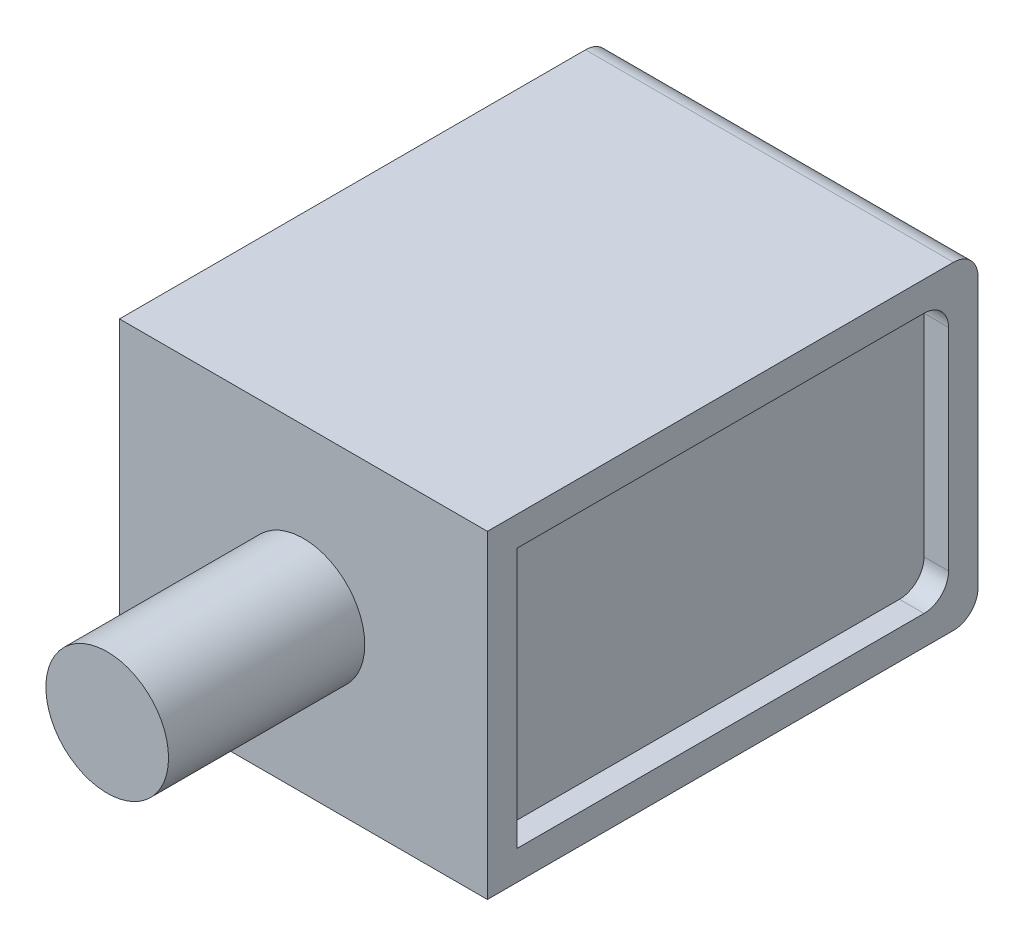
SolidWorks part; units mm, degrees
ref_plane "Plan de face" through (0, 0, 0) normal (0, 0, 1) x (1, 0, 0)
ref_plane "Plan de dessus" through (0, 0, 0) normal (0, 1, 0) x (1, 0, 0)
ref_plane "Plan de droite" through (0, 0, 0) normal (1, 0, 0) x (0, 0, -1)
sketch "Esquisse1" plane through (0, 0, 0) normal (0, 0, 1) x (1, 0, 0)
  line L1 (7.5, -6.5) -> (-7.5, -6.5)
  line L2 (7.5, -6.5) -> (7.5, 6.5)
  line L3 (7.5, 6.5) -> (-7.5, 6.5)
  line L4 (-7.5, -6.5) -> (-7.5, 6.5)
  line L5 (7.5, -6.5) -> (-7.5, 6.5) construction
  line L6 (7.5, 6.5) -> (-7.5, -6.5) construction
  point P0 (0, 0)
  dimension "D1" = 13
  dimension "D2" = 15
extrude "Boss.-Extru.1" add sketch "Esquisse1" along normal mid plane 20
fillet "Congé1" radius 1 2 edges at (0, -6.5, -10) (0, 6.5, -10)
sketch "Esquisse2" plane through (7.5, 0, 0) normal (1, 0, 0) x (0, 0, -1)
  line L8 (-8.8, -5.3) -> (8.8, -5.3)
  line L9 (8.8, -5.3) -> (8.8, 5.3)
  line L10 (8.8, 5.3) -> (-8.8, 5.3)
  line L11 (-8.8, 5.3) -> (-8.8, -5.3)
  line L12 (-8.8, -5.3) -> (8.8, -5.3)
  line L13 (8.8, -5.3) -> (8.8, 5.3)
  line L14 (8.8, 5.3) -> (-8.8, 5.3)
  line L15 (-8.8, 5.3) -> (-8.8, -5.3)
  dimension "D1" = 1.2
extrude "Enlèv. mat.-Extru.1" cut sketch "Esquisse2" against normal blind 1
fillet "Congé2" radius 1 2 edges at (7, -5.3, -8.8) (7, 5.3, -8.8)
mirror "Symétrie1" about plane through (0, 0, 0) normal (1, 0, 0) of "Congé2", "Enlèv. mat.-Extru.1"
sketch "Esquisse3" plane through (0, 0, 10) normal (0, 0, 1) x (1, 0, 0)
  circle A0 centre (0, 0) radius 2.5
  dimension "D1" = 5
extrude "Boss.-Extru.2" add sketch "Esquisse3" along normal blind 8
